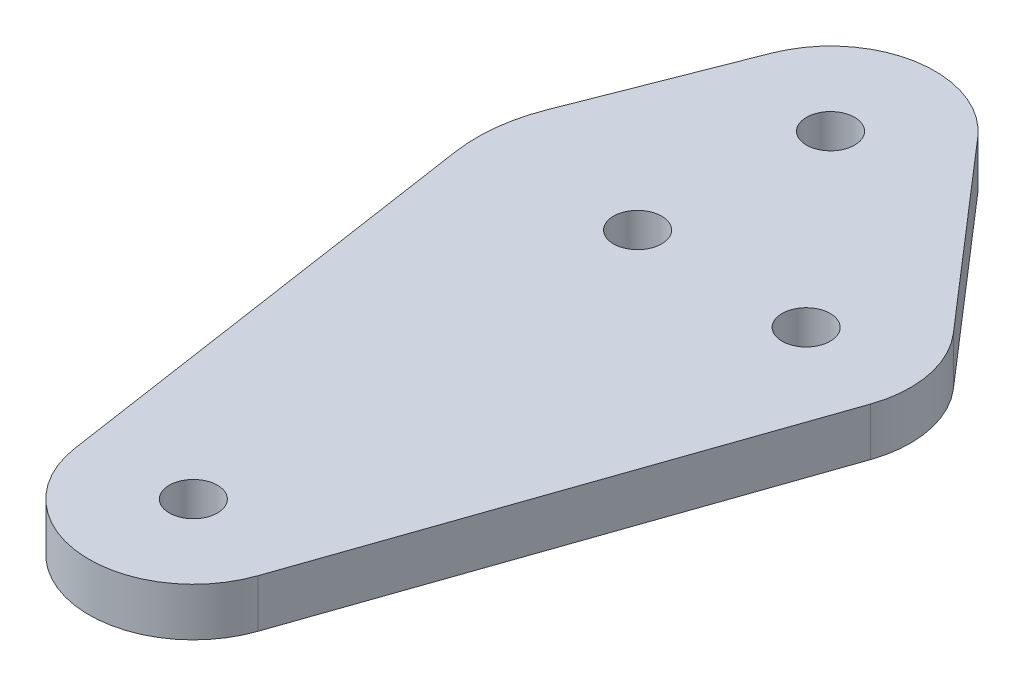
SolidWorks part; units mm, degrees
ref_plane "正面" through (0, 0, 0) normal (0, 0, 1) x (1, 0, 0)
ref_plane "平面" through (0, 0, 0) normal (0, 1, 0) x (1, 0, 0)
ref_plane "右側面" through (0, 0, 0) normal (1, 0, 0) x (0, 0, -1)
sketch "ｽｹｯﾁ1" plane through (0, 0, 0) normal (0, 1, 0) x (1, 0, 0)
  line L0 (-4.9063, 15.5942) -> (4.9135, 4.2552)
  line L1 (6.1419, -2.1276) -> (-3.6779, -30.475)
  line L2 (-15.8725, 13.7084) -> (-19.8119, 3.6453)
  line L3 (-20.3911, -1.472) -> (-16.249, -29.3041)
  circle A0 centre (0, 0) radius 1.5
  circle A1 centre (-9.8198, 11.3389) radius 1.5
  circle A2 centre (-9.8198, -28.3473) radius 1.5
  arc A5 (-4.9063, 15.5942) -> (-15.8725, 13.7084) centre (-9.8198, 11.3389) ccw
  arc A6 (-16.249, -29.3041) -> (-3.6779, -30.475) centre (-9.8198, -28.3473) ccw
  arc A7 (6.1419, -2.1276) -> (4.9135, 4.2552) centre (0, 0) ccw
  arc A8 (-19.8119, 3.6453) -> (-20.3911, -1.472) centre (-10.5, 0) ccw
  circle A9 centre (-10.5, 0) radius 1.5
  point P9 (0, 0)
  point P14 (0, 0)
  dimension "D1" = 3
  dimension "D4" = 5
  dimension "D7" = 10
  dimension "D2" = 15
  dimension "D3" = 30
  dimension "D5" = 10.5
  dimension "D6" = 120
extrude "ﾎﾞｽ - 押し出し1" add sketch "ｽｹｯﾁ1" along normal blind 3
